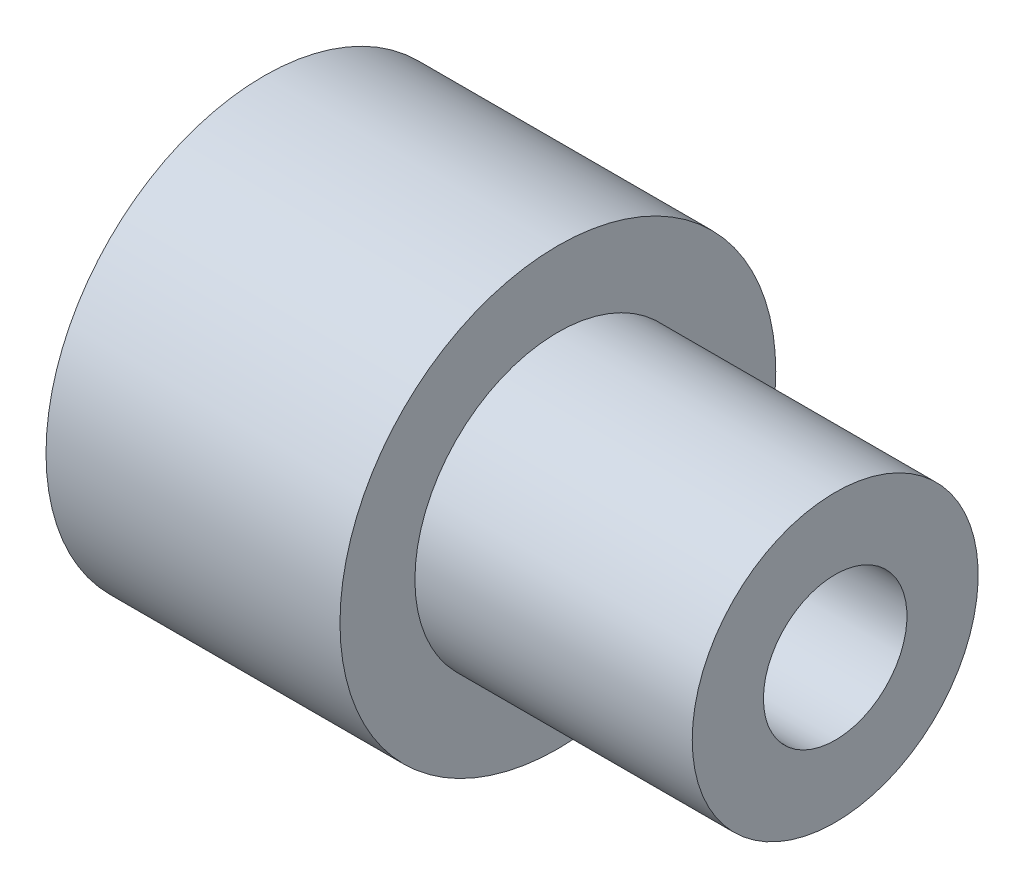
SolidWorks part; units mm, degrees
ref_plane "Piano frontale" through (0, 0, 0) normal (0, 0, 1) x (1, 0, 0)
ref_plane "Piano superiore" through (0, 0, 0) normal (0, 1, 0) x (1, 0, 0)
ref_plane "Piano destro" through (0, 0, 0) normal (1, 0, 0) x (0, 0, -1)
sketch "Schizzo1" plane through (0, 0, 0) normal (0, 0, 1) x (1, 0, 0)
  line L0 (0, 0) -> (9.95, 0) construction
  line L1 (0, 0) -> (0, 3.795)
  line L2 (0, 3.795) -> (5.12, 3.795)
  line L3 (5.12, 3.795) -> (5.12, 2.49)
  line L4 (5.12, 2.49) -> (9.95, 2.49)
  line L5 (9.95, 2.49) -> (9.95, 0)
  line L6 (0, 0) -> (9.95, 0)
  dimension "D1" = 5.12
  dimension "D2" = 9.95
  dimension "D3" = 7.59
  dimension "D4" = 4.98
revolve "Rivoluzione1" add sketch "Schizzo1" angle 360 about L0
hole_wizard "Foro filettato M3x0.5-1" positions "Schizzo3" profile "Schizzo2" tap size "M3x0.5" standard "Ansi Metric" end condition through all
sketch "Schizzo3" plane through (0, 0, 0) normal (-1, 0, 0) x (0, 0, 1)
  point P0 (0, 0)
sketch "Schizzo2" plane through (0, 0, 0) normal (0, 1, 0) x (0, 0, 1)
  line L0 (0, 0) -> (0, 9.95)
  line L1 (0, 9.95) -> (1.25, 9.95)
  line L2 (1.25, 9.95) -> (1.25, 0)
  line L5 (1.25, 0) -> (0, 0)
  line L11 (0, -6.35) -> (0, 107.95) construction
  dimension "Thru Tap Drill Dia." = 2.5
  dimension "Thru Tap Drill Depth" = 9.95
cosmetic thread "Filettatura del foro1" parameters "D2"=3
